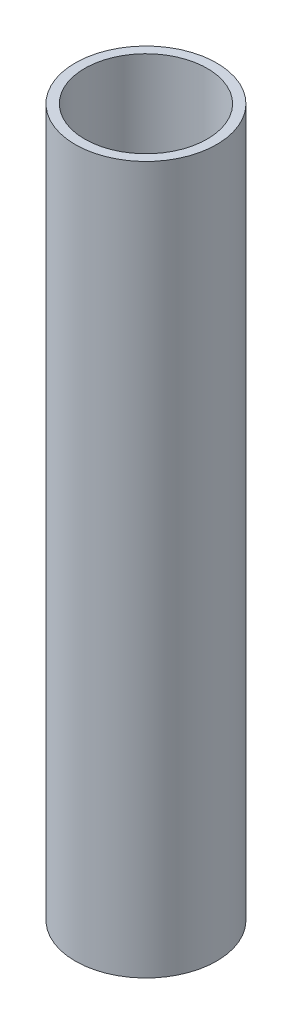
SolidWorks part; units mm, degrees
material "Hexcel AS4C (3000 Filaments)"
ref_plane "Front Plane" through (0, 0, 0) normal (0, 0, 1) x (1, 0, 0)
ref_plane "Top Plane" through (0, 0, 0) normal (0, 1, 0) x (1, 0, 0)
ref_plane "Right Plane" through (0, 0, 0) normal (1, 0, 0) x (0, 0, -1)
sketch "Sketch2" plane through (0, 0, 0) normal (0, 1, 0) x (1, 0, 0)
  circle A0 centre (0, 0) radius 15
  circle A1 centre (0, 0) radius 13
  dimension "D1" = 30
  dimension "D2" = 26
extrude "Boss-Extrude1" add sketch "Sketch2" along normal blind 150
